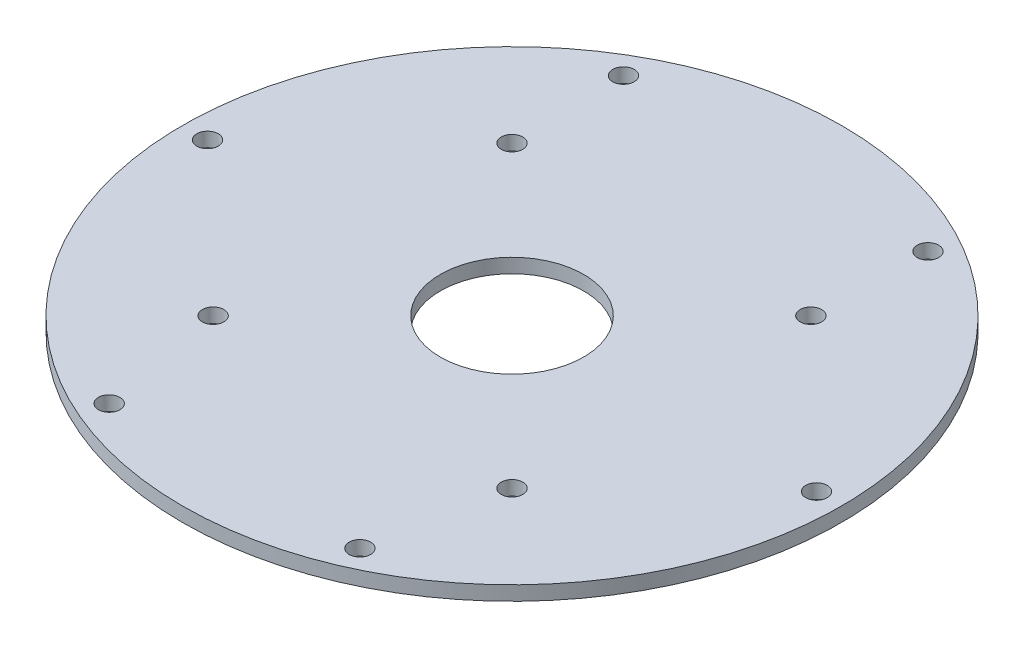
SolidWorks part; units mm, degrees
material "6061 合金"
ref_plane "前视基准面" through (0, 0, 0) normal (0, 0, 1) x (1, 0, 0)
ref_plane "上视基准面" through (0, 0, 0) normal (0, 1, 0) x (1, 0, 0)
ref_plane "右视基准面" through (0, 0, 0) normal (1, 0, 0) x (0, 0, -1)
sketch "草图1" plane through (0, 0, 0) normal (0, 1, 0) x (1, 0, 0)
  circle A0 centre (0, 0) radius 46
  dimension "D1" = 92
extrude "凸台-拉伸1" add sketch "草图1" along normal blind 2
sketch "草图2" plane through (0, 2, 0) normal (0, 1, 0) x (1, 0, 0)
  line L0 (0, 42.5) -> (0, 0) construction
  line L1 (0, 0) -> (-21.25, 36.8061) construction
  circle A0 centre (0, 0) radius 42.5 construction
  circle A1 centre (-21.25, 36.8061) radius 1.5
  circle A2 centre (21.25, 36.8061) radius 1.5
  circle A3 centre (42.5, 0) radius 1.5
  circle A6 centre (-42.5, 0) radius 1.5
  circle A7 centre (-21.25, -36.8061) radius 1.5 [skipped]
  circle A8 centre (21.25, -36.8061) radius 1.5 [skipped]
  circle A9 centre (-17.5, -38.7298) radius 1.5
  circle A10 centre (17.5, -38.7298) radius 1.5
  point P19 (0, 0)
  dimension "D1" = 85
  dimension "D2" = 3
  dimension "D5" = 3
  dimension "D6" = 35
  dimension "D3" = 30
  dimension "D4" = 6
extrude "切除-拉伸1" cut sketch "草图2" against normal through all
sketch "草图3" plane through (0, 2, 0) normal (0, 1, 0) x (1, 0, 0)
  line L0 (0, -38.821) -> (0, 0) construction
  line L1 (0, 0) -> (-20.8597, -20.8597) construction
  circle A0 centre (0, 0) radius 29.5 construction
  circle A1 centre (-20.8597, -20.8597) radius 1.5
  circle A2 centre (-20.8597, 20.8597) radius 1.5
  circle A3 centre (20.8597, 20.8597) radius 1.5
  circle A4 centre (20.8597, -20.8597) radius 1.5
  point P15 (0, 0)
  dimension "D1" = 59
  dimension "D2" = 3
  dimension "D3" = 45
  dimension "D4" = 4
extrude "切除-拉伸2" cut sketch "草图3" against normal through all
sketch "草图4" plane through (0, 2, 0) normal (0, 1, 0) x (1, 0, 0)
  circle A0 centre (0, 0) radius 10
  dimension "D1" = 20
extrude "切除-拉伸3" cut sketch "草图4" against normal through all
